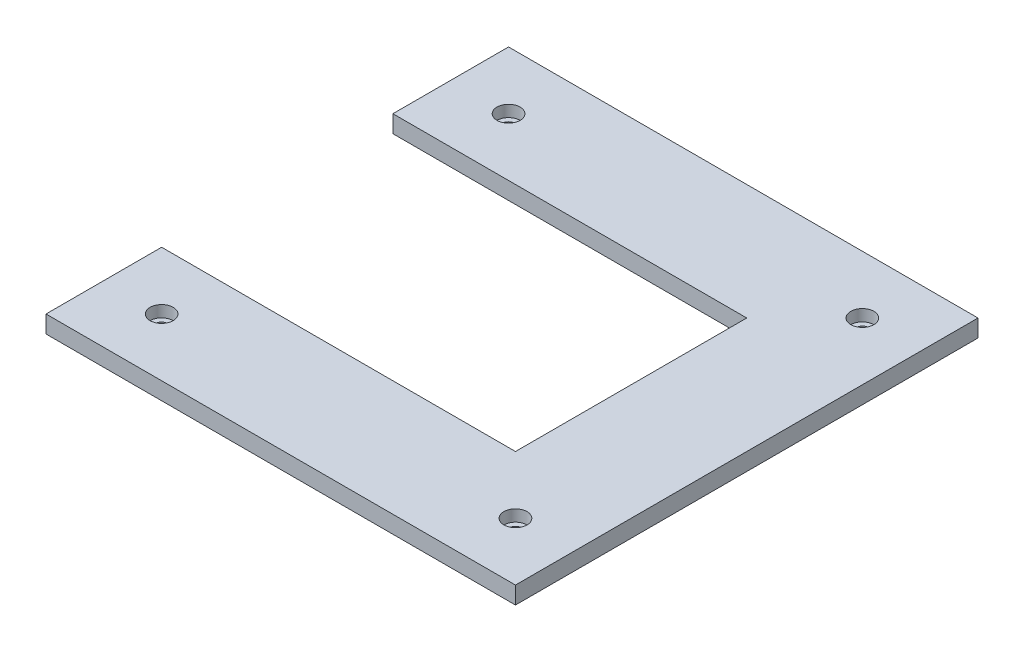
SolidWorks part; units mm, degrees
ref_plane "Front Plane" through (0, 0, 0) normal (0, 0, 1) x (1, 0, 0)
ref_plane "Top Plane" through (0, 0, 0) normal (0, 1, 0) x (1, 0, 0)
ref_plane "Right Plane" through (0, 0, 0) normal (1, 0, 0) x (0, 0, -1)
sketch "Sketch1" plane through (0, 0, 0) normal (0, 1, 0) x (1, 0, 0)
  line L0 (0, 80) -> (0, -80)
  line L1 (0, 80) -> (-162.4, 80)
  line L2 (0, -80) -> (-162.4, -80)
  point P4 (0, 0)
  dimension "D1" = 160
  dimension "D2" = 162.4
extrude "Extrude-Thin1" add sketch "Sketch1" along normal blind 6 thin
sketch "Sketch2" plane through (0, 6, 0) normal (0, 1, 0) x (1, 0, 0)
  line L0 (-162.4, 60) -> (0, 60) construction
  line L1 (-162.4, 40) -> (-162.4, 80) construction
  line L2 (0, 80) -> (0, -80) construction
  line L3 (-162.4, -60) -> (0, -60) construction
  line L4 (-162.4, -80) -> (-162.4, -40) construction
  line L5 (-20, -80) -> (-20, 80) construction
  line L6 (0, -80) -> (-162.4, -80) construction
  line L7 (-162.4, 80) -> (0, 80) construction
  point P18 (-142.4, 60)
  point P20 (-142.4, -60)
  point P27 (-20, 60)
  point P29 (-20, -60)
  dimension "D1" = 20
  dimension "D2" = 20
hole_wizard "CBORE for M4 SHCS1" positions "Sketch2" profile "Sketch3" counterbore size "M4" standard "ANSI Metric" end condition up to next
sketch "Sketch3" plane through (-20, 6, 60) normal (1, 0, 0) x (0, 0, 1)
  line L0 (0, 0) -> (0, 6)
  line L1 (0, 6) -> (2.25, 6)
  line L3 (2.25, 6) -> (2.25, 4)
  line L4 (2.25, 4) -> (4, 4)
  line L5 (4, 4) -> (4, 0)
  line L7 (4, 0) -> (0, 0)
  line L11 (0, -6.35) -> (0, 107.95) construction
  dimension "Thru Hole Dia." = 4.5
  dimension "Thru Hole Depth" = 6
  dimension "C'Bore Dia." = 8
  dimension "C'Bore Depth" = 4
